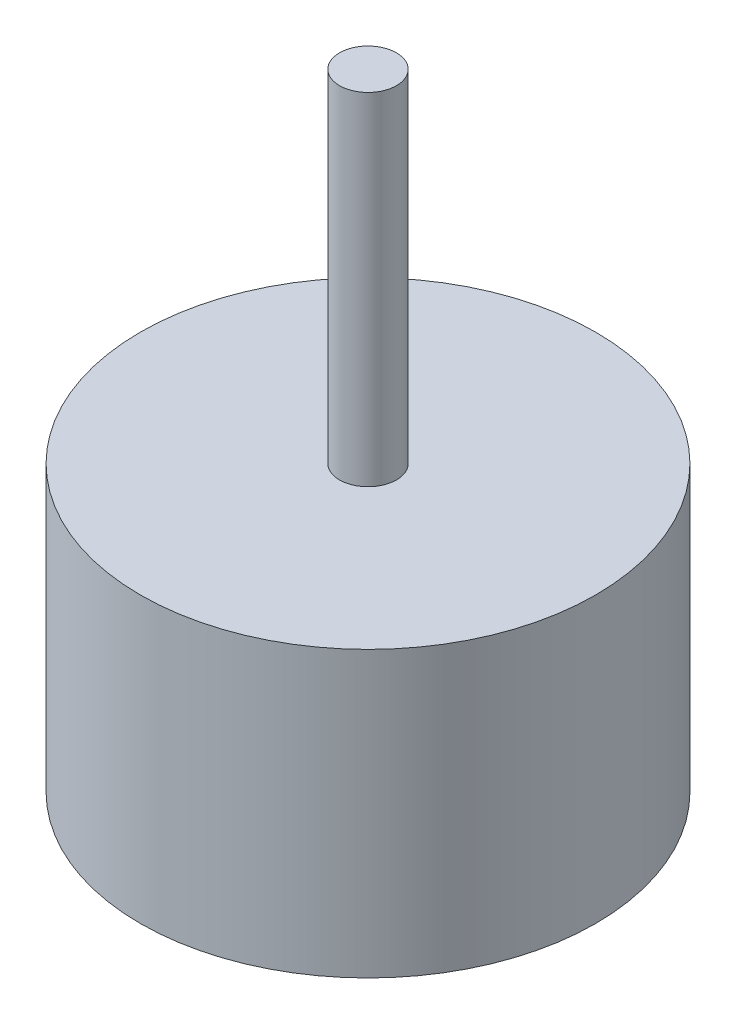
SolidWorks part; units mm, degrees
ref_plane "前视基准面" through (0, 0, 0) normal (0, 0, 1) x (1, 0, 0)
ref_plane "上视基准面" through (0, 0, 0) normal (0, 1, 0) x (1, 0, 0)
ref_plane "右视基准面" through (0, 0, 0) normal (1, 0, 0) x (0, 0, -1)
sketch "草图1" plane through (0, 0, 0) normal (0, 1, 0) x (1, 0, 0)
  circle A0 centre (0, 0) radius 20
  dimension "D1" = 40
extrude "凸台-拉伸1" add sketch "草图1" along normal blind 25
sketch "草图2" plane through (0, 25, 0) normal (0, 1, 0) x (1, 0, 0)
  circle A0 centre (0, 0) radius 2.5
  dimension "D1" = 5
extrude "凸台-拉伸2" add sketch "草图2" along normal blind 30
